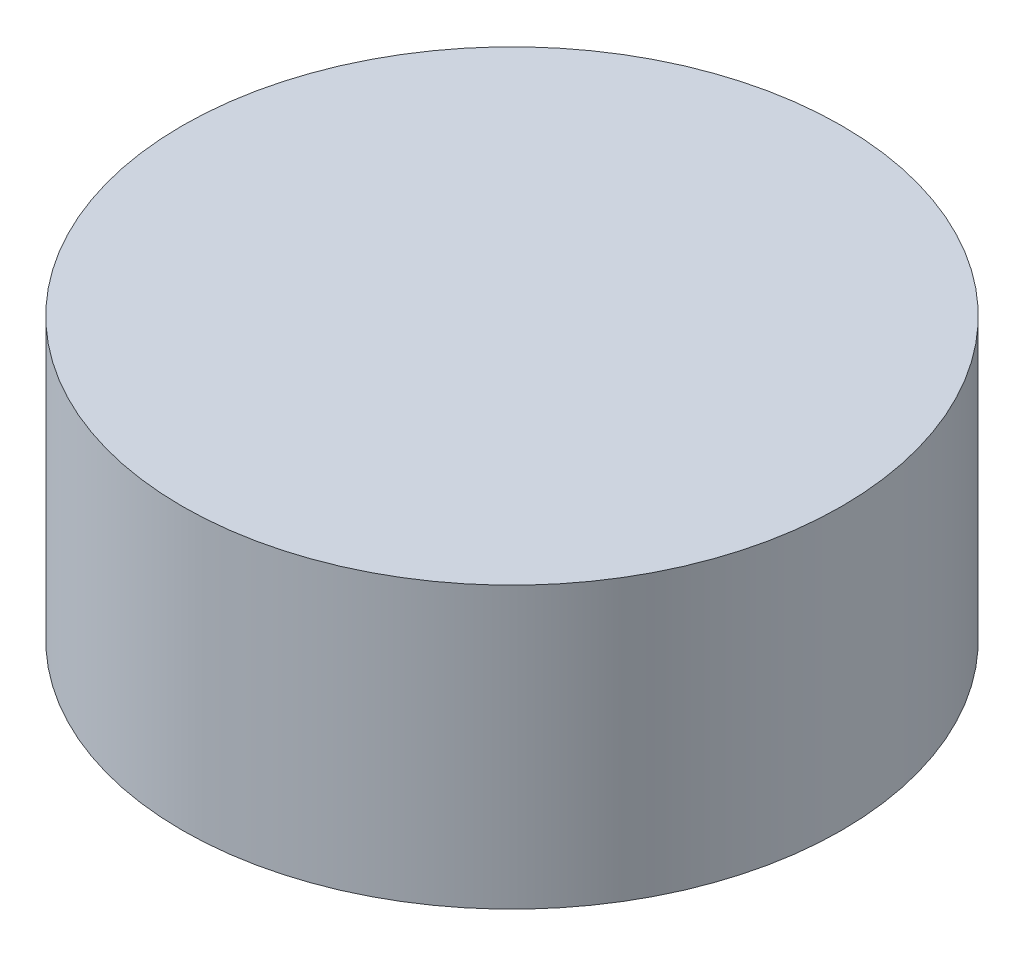
SolidWorks part; units mm, degrees
material "Copper"
ref_plane "Front Plane" through (0, 0, 0) normal (0, 0, 1) x (1, 0, 0)
ref_plane "Top Plane" through (0, 0, 0) normal (0, 1, 0) x (1, 0, 0)
ref_plane "Right Plane" through (0, 0, 0) normal (1, 0, 0) x (0, 0, -1)
sketch "Sketch1" plane through (0, 0, 0) normal (0, 1, 0) x (1, 0, 0)
  circle A0 centre (0, 0) radius 1.175
extrude "Boss-Extrude1" add sketch "Sketch1" along normal blind 1
